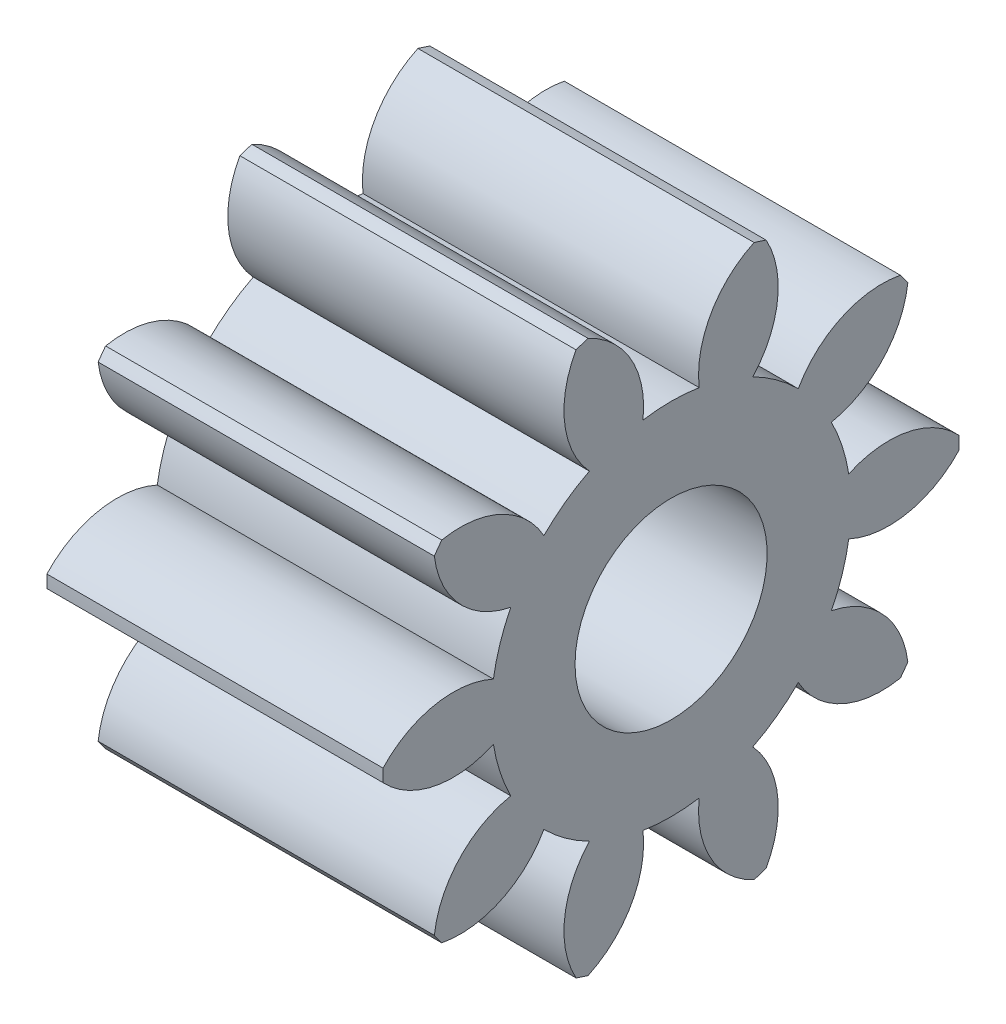
SolidWorks part; units mm, degrees
ref_plane "Plane1" through (0, 0, 0) normal (0, 0, 1) x (1, 0, 0)
ref_plane "Plane2" through (0, 0, 0) normal (0, 1, 0) x (1, 0, 0)
ref_plane "Plane3" through (0, 0, 0) normal (1, 0, 0) x (0, 0, -1)
sketch "HoldingSke" plane through (0, 0, 0) normal (0, 1, 0) x (1, 0, 0)
  line L0 (0, 0) -> (3.9392, -0.6946)
  line L1 (-15, 0) -> (100, 0) construction
  line L2 (0, 0) -> (-2.1039, 2.3779)
  line L3 (0, 0) -> (-11.863, 4.5341)
  line L4 (0, 0) -> (8.5048, 1.4996)
  line L5 (0, 0) -> (-46.8476, -17.4728)
  line L6 (0, 0) -> (-1.4507, -0.9788)
  line L7 (-2.1039, 2.3779) -> (8.6586, 51.2059)
  line L8 (-76.2, 54.61) -> (-76.1, 54.61)
  line L9 (-71.009, 38.7566) -> (-53.1078, 45.2721)
  line L10 (-76.2, 71.12) -> (104.1128, 71.12)
  line L11 (0, 0) -> (-1.75, 0)
  line L12 (-76.2, 101.6) -> (-76.192, 101.6)
  line L13 (24.9733, 27.94) -> (52.9518, 28.4284)
  line L14 (24.9733, 27.94) -> (24.9743, 27.94)
  line L15 (24.9733, 27.94) -> (100.4006, 29.5858)
  line L16 (-63.627, -0.25) -> (-12.827, -0.25)
  circle A0 centre (0, 0) radius 0.5
  circle A1 centre (0, 0) radius 0.9365
  circle A2 centre (0, 0) radius 37.5
  circle A3 centre (0, 0) radius 0.5
  dimension "MHD" = 1.873
  dimension "Hub_dia" = 75
  dimension "Bore" = 1
  dimension "MBD" = 1
  dimension "Num_teeth" = 10
  dimension "Pitch" = 4
  dimension "Overall_len" = 50
  dimension "Show_teeth" = 10
  dimension "Thickness" = 1.75
  dimension "OAL" = 50.0001
  dimension "T_dim" = 0.1
  dimension "Ap" = 20
  dimension "H" = 19.05
  dimension "Pitch_radius" = 180.3128
  dimension "Width" = 1.75
  dimension "Backlash" = 0.008
  dimension "Addendum_fac" = 1
  dimension "Dedendum_fac" = 1.25
  dimension "Clearance_fac" = 0.25
  dimension "Dedendum_add" = 0.001
  dimension "Module" = 0.25
sketch "BasProSke" plane through (0, 0, 0) normal (0, 1, 0) x (1, 0, 0)
  line L0 (-10, 0) -> (60, 0) construction
  line L1 (0, 0) -> (0, 1.5)
  line L2 (0, 0) -> (1.75, 0)
  line L3 (1.75, 0) -> (1.75, 1.5)
  line L4 (1.75, 1.5) -> (0, 1.5)
  dimension "Thickness" = 1.75
  dimension "Diameter" = 3
revolve "Base-Revolve" add sketch "BasProSke" angle 360 about L0
sketch "TooCutSke" plane through (0, 0, 0) normal (1, 0, 0) x (0, 0, -1)
  line L1 (0, 0) -> (0, 107) construction
  line L2 (0, 0) -> (-0.2095, 1.2323) construction
  line L3 (0, 0) -> (-0.7644, 2.3524) construction
  line L4 (-0.2095, 1.2323) -> (-0.3822, 1.1762) construction
  arc A0 (0.1463, 0.925) -> (-0.1463, 0.925) centre (0, 0) ccw
  arc A1 (0.4686, 1.4516) -> (-0.4686, 1.4516) centre (0, 0) ccw
  circle A2 centre (0, 0) radius 1.25 construction
  circle A3 centre (0, 0) radius 1.1746 construction
  arc A4 (-0.1463, 0.925) -> (-0.4686, 1.4516) centre (-0.6429, 0.983) ccw
  arc A5 (0.4686, 1.4516) -> (0.1463, 0.925) centre (0.6429, 0.983) ccw
  dimension "Root_dia" = 1.873
  dimension "Overcut_dia" = 3.0508
  dimension "Pitch_dia" = 2.5
  dimension "Base_dia" = 2.3492
  dimension "Flank_rad" = 0.5
  dimension "Half_ang" = 18
  dimension "Half_CT" = 0.1815
extrude "ToothCut" cut sketch "TooCutSke" along normal through all
fillet "Breaks" [suppressed] radius 0.005
fillet "RootFillets" [suppressed] radius 0.0635
pattern_circular "TeethCuts" count 10 every 36 about axis through (-10, 0, 0) along (1, 0, 0) of "ToothCut", "RootFillets", "Breaks"
sketch "HubNeaOneSke" plane through (0, 0, 0) normal (-1, 0, 0) x (0, 0, 1)
  circle A0 centre (0, 0) radius 0.9365
  dimension "Diameter" = 1.873
extrude "HubNearOne" [suppressed] add sketch "HubNeaOneSke" along normal blind 48.2501
sketch "HubNeaBotSke" plane through (0, 0, 0) normal (-1, 0, 0) x (0, 0, 1)
  circle A0 centre (0, 0) radius 0.9365
  dimension "Diameter" = 1.873
extrude "HubNearBoth" [suppressed] add sketch "HubNeaBotSke" along normal blind 24.125
ref_plane "FarPln" through (1.75, 0, 0) normal (1, 0, 0) x (0, 0, -1)
sketch "HubFarSke" plane through (1.75, 0, 0) normal (1, 0, 0) x (0, 0, -1)
  circle A0 centre (0, 0) radius 0.9365
  dimension "Diameter" = 1.873
extrude "HubFar" [suppressed] add sketch "HubFarSke" along normal blind 24.125
sketch "BorSke" plane through (0, 0, 0) normal (1, 0, 0) x (0, 0, -1)
  circle A0 centre (0, 0) radius 0.5
  dimension "Diameter" = 1
extrude "Bore" cut sketch "BorSke" along normal mid plane 100.0001
sketch "KeySke" plane through (0, 0, 0) normal (1, 0, 0) x (0, 0, -1)
  line L0 (-0.05, 0) -> (-0.05, 0.6)
  line L1 (-0.05, 0.6) -> (0.05, 0.6)
  line L2 (0.05, 0.6) -> (0.05, 0)
  line L3 (0, 0) -> (0, 34) construction
  line L4 (-0.05, 0) -> (0.05, 0)
  dimension "Offset" = 0.6
  dimension "Width" = 0.1
extrude "Keyway" [suppressed] cut sketch "KeySke" along normal mid plane 100.0001
pattern_circular "Keyway2" [suppressed] count 2 every 90 about axis through (-10, 0, 0) along (1, 0, 0)
equation "' \"Module@HoldingSke\" = 6.35"
equation "' \"Num_teeth@HoldingSke\" = 12"
equation "' \"Ap@HoldingSke\" =  20"
equation "' \"Ap@HoldingSke\" = 20"
equation "' \"Width@HoldingSke\" = 0.5 * 25.4"
equation "' \"Hub_dia@HoldingSke\"= 1 * 25.4"
equation "' \"Hub_dia@HoldingSke\" = 1 * 25.4"
equation "' \"Overall_len@HoldingSke\" = 1.0 * 25.4"
equation "' \"Bore@HoldingSke\" = 0.75 * 25.4"
equation "' \"T_dim@HoldingSke\" = 0.1 * 25.4"
equation "' \"Width@KeySke\" = 0.25 * 25.4"
equation "' \"Show_teeth@HoldingSke\" = 13"
equation "' \"Backlash@HoldingSke\" = 0.009 * 25.4"
equation "' \"Addendum_fac@HoldingSke\" = 1.0"
equation "' \"Dedendum_fac@HoldingSke\" = 1.25"
equation "' \"Dedendum_add@HoldingSke\" = 0.00005 * 25.4"
equation "' \"Clearance_fac@HoldingSke\" = 0.25"
equation "\"Pitch@HoldingSke\" = 1 / \"Module@HoldingSke\""
equation "\"Overcut_dia@TooCutSke\" = (\"Num_teeth@HoldingSke\" + 2 * \"Addendum_fac@HoldingSke\") / \"Pitch@HoldingSke\" + 0.002 * 25.4"
equation "\"Pitch_dia@TooCutSke\" = \"Num_teeth@HoldingSke\" / \"Pitch@HoldingSke\""
equation "\"Base_dia@TooCutSke\" = \"Num_teeth@HoldingSke\" / \"Pitch@HoldingSke\" * cos((\"Ap@HoldingSke\"  * 3.14159265 / 180))"
equation "\"Root_dia@TooCutSke\" = (\"Num_teeth@HoldingSke\" + 2) / \"Pitch@HoldingSke\" - 2 * (\"Addendum_fac@HoldingSke\" + \"Dedendum_fac@HoldingSke\") / \"Pitch@HoldingSke\" - \"Dedendum_add@HoldingSke\" * 2"
equation "\"Half_ang@TooCutSke\" = 180 / \"Num_teeth@HoldingSke\""
equation "\"Half_CT@TooCutSke\" = \"Num_teeth@HoldingSke\" / \"Pitch@HoldingSke\" * sin((3.14159265 / 2 / \"Num_teeth@HoldingSke\")) / 2 - 7 * \"Backlash@HoldingSke\" / 4"
equation "\"Flank_rad@TooCutSke\" = \"Num_teeth@HoldingSke\" / \"Pitch@HoldingSke\" / 5"
equation "\"Radius@RootFillets\" = \"Clearance_fac@HoldingSke\" / \"Pitch@HoldingSke\" + \"Dedendum_add@HoldingSke\""
equation "\"Break_rad@Breaks\" = 0.02 / \"Pitch@HoldingSke\""
equation "\"Thickness@HoldingSke\" = \"Width@HoldingSke\""
equation "\"OAL@HoldingSke\" = \"Thickness@HoldingSke\""
equation "\"MHD@HoldingSke\" = (\"Num_teeth@HoldingSke\" + 2) / \"Pitch@HoldingSke\" - 2 * (\"Addendum_fac@HoldingSke\" + \"Dedendum_fac@HoldingSke\")  / \"Pitch@HoldingSke\" - \"Dedendum_add@HoldingSke\" * 2"
equation "\"MBD@HoldingSke\" = (\"Num_teeth@HoldingSke\" + 2) / \"Pitch@HoldingSke\" - 2 * (\"Addendum_fac@HoldingSke\" + \"Dedendum_fac@HoldingSke\")  / \"Pitch@HoldingSke\" - \"Dedendum_add@HoldingSke\" * 2 - 0.002 * 25.4"
equation "\"MHD@HoldingSke\" = ((sgn( \"MHD@HoldingSke\" - \"Hub_dia@HoldingSke\" )-1)*( \"MHD@HoldingSke\" - \"Hub_dia@HoldingSke\" ))/-2+ \"Hub_dia@HoldingSke\""
equation "\"MBD@HoldingSke\" = ((sgn( \"MBD@HoldingSke\" - \"Bore@HoldingSke\" )-1)*( \"MBD@HoldingSke\" - \"Bore@HoldingSke\" ))/-2+ \"Bore@HoldingSke\""
equation "\"OAL@HoldingSke\" = ((sgn( \"OAL@HoldingSke\" - \"Overall_len@HoldingSke\" )+1)*( \"OAL@HoldingSke\" - \"Overall_len@HoldingSke\" ))/2 + \"Overall_len@HoldingSke\" + 0.000002 * 25.4"
equation "\"Num_teeth@TeethCuts\" = int( \"Show_teeth@HoldingSke\" ) + 1"
equation "\"Num_teeth@TeethCuts\" = ((sgn( \"Num_teeth@TeethCuts\" - \"Num_teeth@HoldingSke\" )-1)*( \"Num_teeth@TeethCuts\" - \"Num_teeth@HoldingSke\" ))/-2+ \"Num_teeth@HoldingSke\""
equation "\"Num_teeth@TeethCuts\" = ((sgn( \"Num_teeth@TeethCuts\" - 2.0)+1)*( \"Num_teeth@TeethCuts\" - 2.0))/2 +2.0"
equation "\"Angle@TeethCuts\" = 360.0 / \"Num_teeth@HoldingSke\""
equation "\"Diameter@BasProSke\" = (\"Num_teeth@HoldingSke\" + 2 * \"Addendum_fac@HoldingSke\") / \"Pitch@HoldingSke\""
equation "\"Thickness@BasProSke\"  = \"Thickness@HoldingSke\""
equation "' \"Fillet_rad@BasProSke\" =  \"Thickness@HoldingSke\" * 0.05"
equation "' \"Fillet_rad@BasProSke\" = \"Thickness@HoldingSke\" * 0.05"
equation "\"MHD@HoldingSke\" = ((sgn( \"MHD@HoldingSke\" - \"Root_dia@TooCutSke\" )-1)*( \"MHD@HoldingSke\" - \"Root_dia@TooCutSke\" ))/-2+ \"Root_dia@TooCutSke\""
equation "\"Diameter@HubNeaOneSke\" = \"MHD@HoldingSke\""
equation "\"Length@HubNearOne\" = \"OAL@HoldingSke\" - \"Thickness@BasProSke\""
equation "\"Diameter@HubNeaBotSke\" = \"MHD@HoldingSke\""
equation "\"Length@HubNearBoth\" = ( \"OAL@HoldingSke\" - \"Thickness@BasProSke\" ) / 2.0"
equation "\"Thickness@FarPln\" = \"Thickness@BasProSke\""
equation "\"Diameter@HubFarSke\" = \"MHD@HoldingSke\""
equation "\"Length@HubFar\" = ( \"OAL@HoldingSke\" - \"Thickness@BasProSke\" ) / 2.0"
equation "\"Diameter@BorSke\" = \"MBD@HoldingSke\""
equation "\"D1@Bore\" = \"OAL@HoldingSke\" * 2.0"
equation "\"D1@Keyway\" = \"OAL@HoldingSke\" * 2.0"
equation "\"Offset@KeySke\" = \"T_dim@HoldingSke\" + \"MBD@HoldingSke\" / 2.0"
